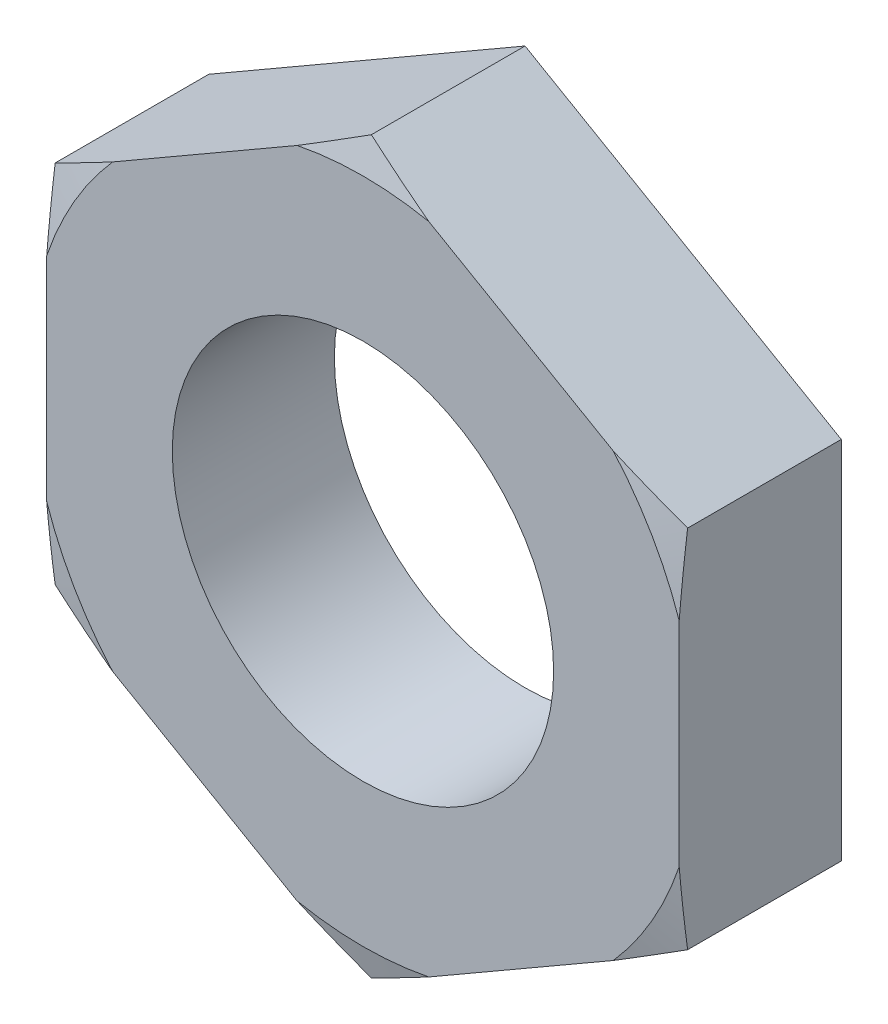
SolidWorks part; units mm, degrees
material "A3"
ref_plane "基准面1" through (0, 0, 0) normal (0, 0, 1) x (1, 0, 0)
ref_plane "基准面2" through (0, 0, 0) normal (0, 1, 0) x (1, 0, 0)
ref_plane "基准面3" through (0, 0, 0) normal (1, 0, 0) x (0, 0, -1)
sketch "尺寸草图" plane through (0, 0, 0) normal (0, 0, 1) x (1, 0, 0)
  line L0 (0, 0) -> (9.2444, 0)
  point P3 (4, 0)
  point P4 (1.7, 0)
  point P5 (7, 0)
  point P6 (5.1072, 0)
  point P7 (4.0801, 0)
  point P8 (7.66, 0)
  dimension "D" = 4
  dimension "e" = 7.66
  dimension "m" = 1.7
  dimension "s" = 7
sketch "草图1" plane through (0, 0, 0) normal (0, 0, 1) x (1, 0, 0)
  line L0 (0, 20.0172) -> (0, -14.298) construction
  line L1 (-13.2257, 0) -> (13.2257, 0) construction
  line L3 (0, 3.83) -> (-3.3169, 1.915)
  line L4 (-3.3169, 1.915) -> (-3.3169, -1.915)
  line L5 (-3.3169, -1.915) -> (0, -3.83)
  line L6 (0, -3.83) -> (3.3169, -1.915)
  line L7 (3.3169, -1.915) -> (3.3169, 1.915)
  line L8 (3.3169, 1.915) -> (0, 3.83)
  circle A0 centre (0, 0) radius 3.3169 construction
  circle A1 centre (0, 0) radius 2
  dimension "D" = 4
  dimension "e" = 7.66
extrude "基体-拉伸" add sketch "草图1" along normal blind 1.7
cosmetic thread "装饰螺纹线1"
chamfer "倒角1" [suppressed] distance 0.1667 angle 45
sketch "草图2" plane through (0, 0, 1.7) normal (0, 0, 1) x (1, 0, 0)
  circle A0 centre (0, 0) radius 3.5
  dimension "s" = 7
extrude "切除-拉伸1" cut sketch "草图2" against normal through all draft 75 flip side to cut
equation "\"D@草图1\" = \"D@尺寸草图\""
equation "\"m@基体-拉伸\" = \"m@尺寸草图\""
equation "\"e@草图1\" = \"e@尺寸草图\""
equation "\"s@草图2\" = \"s@尺寸草图\""
equation "\"D1@倒角1\" = \"D@草图1\"/24"
equation "\"D2@装饰螺纹线1\" = \"D@草图1\"-\"D@草图1\"/24"
